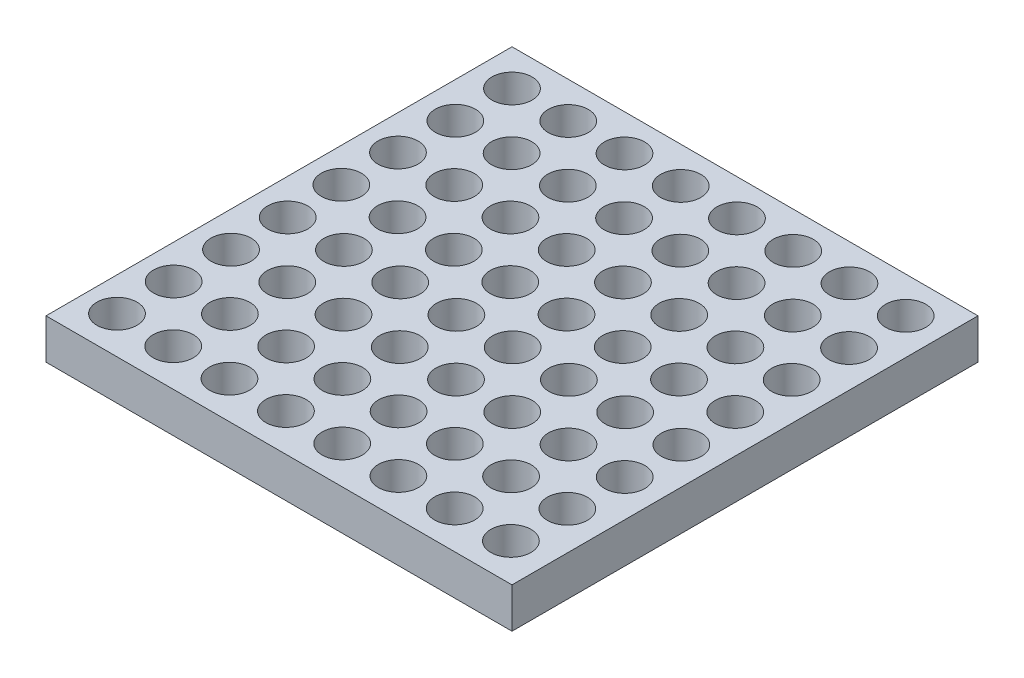
SolidWorks part; units mm, degrees
ref_plane "Front Plane" through (0, 0, 0) normal (0, 0, 1) x (1, 0, 0)
ref_plane "Top Plane" through (0, 0, 0) normal (0, 1, 0) x (1, 0, 0)
ref_plane "Right Plane" through (0, 0, 0) normal (1, 0, 0) x (0, 0, -1)
sketch "Sketch2" plane through (0, 0, 0) normal (0, 1, 0) x (1, 0, 0)
  line L1 (-29, 29) -> (29, 29)
  line L2 (-29, 29) -> (-29, -29)
  line L3 (-29, -29) -> (29, -29)
  line L4 (29, 29) -> (29, -29)
extrude "Boss-Extrude1" add sketch "Sketch2" along normal blind 5
sketch "Sketch3" plane through (0, 5, 0) normal (0, 1, 0) x (1, 0, 0)
  line L0 (-29, 29) -> (-29, -29) construction
  line L1 (29, 29) -> (-29, 29) construction
  circle A0 centre (-24.5, 24.5) radius 2.5
  circle A1 centre (-17.5, 24.5) radius 2.5
  circle A2 centre (-10.5, 24.5) radius 2.5
  circle A3 centre (-3.5, 24.5) radius 2.5
  circle A4 centre (3.5, 24.5) radius 2.5
  circle A5 centre (10.5, 24.5) radius 2.5
  circle A6 centre (17.5, 24.5) radius 2.5
  circle A7 centre (24.5, 24.5) radius 2.5
  circle A8 centre (-24.5506, 17.5002) radius 2.5
  circle A9 centre (-17.5506, 17.5002) radius 2.5
  circle A10 centre (-10.5506, 17.5002) radius 2.5
  circle A11 centre (-3.5506, 17.5002) radius 2.5
  circle A12 centre (3.4494, 17.5002) radius 2.5
  circle A13 centre (10.4494, 17.5002) radius 2.5
  circle A14 centre (17.4494, 17.5002) radius 2.5
  circle A15 centre (24.4494, 17.5002) radius 2.5
  circle A16 centre (-24.6934, 10.5002) radius 2.5
  circle A17 centre (-17.6934, 10.5002) radius 2.5
  circle A18 centre (-10.6934, 10.5002) radius 2.5
  circle A19 centre (-3.6934, 10.5002) radius 2.5
  circle A20 centre (3.3066, 10.5002) radius 2.5
  circle A21 centre (10.3066, 10.5002) radius 2.5
  circle A22 centre (17.3066, 10.5002) radius 2.5
  circle A23 centre (24.3066, 10.5002) radius 2.5
  circle A24 centre (-24.7442, 3.5004) radius 2.5
  circle A25 centre (-17.744, 3.5002) radius 2.5
  circle A26 centre (-10.7442, 3.5004) radius 2.5
  circle A27 centre (-3.744, 3.5273) radius 2.5
  circle A28 centre (3.256, 3.5273) radius 2.5
  circle A29 centre (10.256, 3.5273) radius 2.5
  circle A30 centre (17.256, 3.5273) radius 2.5
  circle A31 centre (24.256, 3.5273) radius 2.5
  circle A32 centre (-24.5615, -3.3594) radius 2.5
  circle A33 centre (-17.5615, -3.3594) radius 2.5
  circle A34 centre (-10.5615, -3.3594) radius 2.5
  circle A35 centre (-3.5615, -3.3594) radius 2.5
  circle A36 centre (3.4385, -3.3594) radius 2.5
  circle A37 centre (10.4385, -3.3594) radius 2.5
  circle A38 centre (17.4385, -3.3594) radius 2.5
  circle A39 centre (24.4385, -3.3594) radius 2.5
  circle A40 centre (-24.612, -10.3592) radius 2.5
  circle A41 centre (-17.612, -10.3592) radius 2.5
  circle A42 centre (-10.612, -10.3592) radius 2.5
  circle A43 centre (-3.612, -10.3592) radius 2.5
  circle A44 centre (3.388, -10.3592) radius 2.5
  circle A45 centre (10.388, -10.3592) radius 2.5
  circle A46 centre (17.388, -10.3592) radius 2.5
  circle A47 centre (24.388, -10.3592) radius 2.5
  circle A48 centre (-24.7548, -17.3592) radius 2.5
  circle A49 centre (-17.7548, -17.3592) radius 2.5
  circle A50 centre (-10.7548, -17.3592) radius 2.5
  circle A51 centre (-3.7548, -17.3592) radius 2.5
  circle A52 centre (3.2452, -17.3592) radius 2.5
  circle A53 centre (10.2452, -17.3592) radius 2.5
  circle A54 centre (17.2452, -17.3592) radius 2.5
  circle A55 centre (24.2452, -17.3592) radius 2.5
  circle A56 centre (-24.8056, -24.359) radius 2.5
  circle A57 centre (-17.8054, -24.3592) radius 2.5
  circle A58 centre (-10.8056, -24.359) radius 2.5
  circle A59 centre (-3.8054, -24.3321) radius 2.5
  circle A60 centre (3.1946, -24.3321) radius 2.5
  circle A61 centre (10.1946, -24.3321) radius 2.5
  circle A62 centre (17.1946, -24.3321) radius 2.5
  circle A63 centre (24.1946, -24.3321) radius 2.5
  point P0 (-24.5, 24.5)
  point P7 (-10.5, 24.5)
  point P8 (-17.5, 24.5)
  point P14 (-3.5, 24.5)
  point P16 (3.5, 24.5)
  point P19 (17.5, 24.5)
  point P20 (10.5, 24.5)
  point P26 (24.5, 24.5)
  point P28 (-24.5506, 17.5002)
  point P31 (-10.5506, 17.5002)
  point P32 (-17.5506, 17.5002)
  point P38 (-3.5506, 17.5002)
  point P40 (3.4494, 17.5002)
  point P43 (17.4494, 17.5002)
  point P44 (10.4494, 17.5002)
  point P50 (24.4494, 17.5002)
  point P52 (-24.6934, 10.5002)
  point P55 (-10.6934, 10.5002)
  point P56 (-17.6934, 10.5002)
  point P62 (-3.6934, 10.5002)
  point P64 (3.3066, 10.5002)
  point P67 (17.3066, 10.5002)
  point P68 (10.3066, 10.5002)
  point P74 (24.3066, 10.5002)
  point P76 (-24.7442, 3.5004)
  point P79 (-10.7442, 3.5004)
  point P80 (-17.744, 3.5002)
  point P86 (-3.744, 3.5273)
  point P88 (3.256, 3.5273)
  point P91 (17.256, 3.5273)
  point P92 (10.256, 3.5273)
  point P98 (24.256, 3.5273)
  point P100 (-24.5615, -3.3594)
  point P103 (-10.5615, -3.3594)
  point P104 (-17.5615, -3.3594)
  point P110 (-3.5615, -3.3594)
  point P112 (3.4385, -3.3594)
  point P115 (17.4385, -3.3594)
  point P116 (10.4385, -3.3594)
  point P122 (24.4385, -3.3594)
  point P124 (-24.612, -10.3592)
  point P127 (-10.612, -10.3592)
  point P128 (-17.612, -10.3592)
  point P134 (-3.612, -10.3592)
  point P136 (3.388, -10.3592)
  point P139 (17.388, -10.3592)
  point P140 (10.388, -10.3592)
  point P146 (24.388, -10.3592)
  point P148 (-24.7548, -17.3592)
  point P151 (-10.7548, -17.3592)
  point P152 (-17.7548, -17.3592)
  point P158 (-3.7548, -17.3592)
  point P160 (3.2452, -17.3592)
  point P163 (17.2452, -17.3592)
  point P164 (10.2452, -17.3592)
  point P170 (24.2452, -17.3592)
  point P172 (-24.8056, -24.359)
  point P175 (-10.8056, -24.359)
  point P176 (-17.8054, -24.3592)
  point P182 (-3.8054, -24.3321)
  point P184 (3.1946, -24.3321)
  point P187 (17.1946, -24.3321)
  point P188 (10.1946, -24.3321)
  point P194 (24.1946, -24.3321)
  dimension "D3" = 7
  dimension "D5" = 7
  dimension "D6" = 7
  dimension "D12" = 4.5
  dimension "D13" = 4.5
  dimension "D1" = 4.5
  dimension "D2" = 4.5
  dimension "D4" = 7
  dimension "D7" = 7
  dimension "D8" = 7
  dimension "D9" = 7
  dimension "D10" = 4.5
  dimension "D11" = 4.5
  dimension "D14" = 7
  dimension "D15" = 7
  dimension "D16" = 7
  dimension "D17" = 7
  dimension "D18" = 7
  dimension "D19" = 7
  dimension "D20" = 7
  dimension "D21" = 7
  dimension "D22" = 7
  dimension "D23" = 7
  dimension "D24" = 7
  dimension "D25" = 7
  dimension "D26" = 7
  dimension "D27" = 7
  dimension "D28" = 7
  dimension "D29" = 7
  dimension "D30" = 7
  dimension "D31" = 7
  dimension "D32" = 7
  dimension "D33" = 7
  dimension "D34" = 7
  dimension "D35" = 7
  dimension "D36" = 7
  dimension "D37" = 7
  dimension "D38" = 7
  dimension "D39" = 7
  dimension "D40" = 7
  dimension "D41" = 7
  dimension "D42" = 7
  dimension "D43" = 7
  dimension "D44" = 7
  dimension "D45" = 7
  dimension "D46" = 7
  dimension "D47" = 7
  dimension "D48" = 7
  dimension "D49" = 7
  dimension "D50" = 7
  dimension "D51" = 7
  dimension "D52" = 7
  dimension "D53" = 7
  dimension "D54" = 7
  dimension "D55" = 7
  dimension "D56" = 7
  dimension "D57" = 7
  dimension "D58" = 7
extrude "Cut-Extrude1" cut sketch "Sketch3" against normal blind 5
